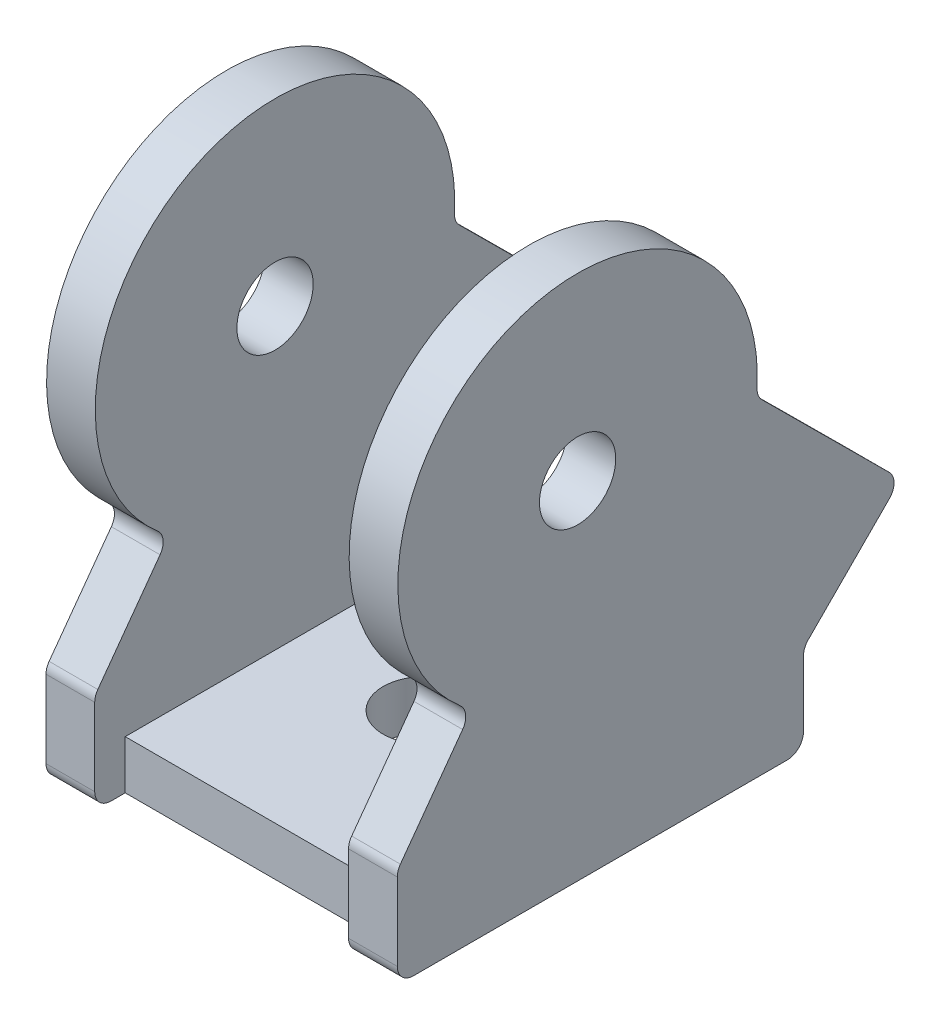
SolidWorks part; units mm, degrees
ref_plane "Front Plane" through (0, 0, 0) normal (0, 0, 1) x (1, 0, 0)
ref_plane "Top Plane" through (0, 0, 0) normal (0, 1, 0) x (1, 0, 0)
ref_plane "Right Plane" through (0, 0, 0) normal (1, 0, 0) x (0, 0, -1)
sketch "Sketch3" plane through (0, 0, 0) normal (0, 1, 0) x (1, 0, 0)
  line L0 (-15.635, 21.24) -> (15.635, -21.24) construction
  line L1 (-15.635, 21.24) -> (15.635, 21.24)
  line L2 (-15.635, 21.24) -> (-15.635, -21.24)
  line L3 (-15.635, -21.24) -> (15.635, -21.24)
  line L4 (15.635, 21.24) -> (15.635, -21.24)
  dimension "D1" = 31.27
  dimension "D2" = 42.48
extrude "Boss-Extrude1" add sketch "Sketch3" along normal blind 6 contours L1 L4 L3 L2
sketch "Sketch4" plane through (15.635, 0, 0) normal (1, 0, 0) x (0, 0, -1)
  line L0 (-24.9979, 0) -> (25.0366, 0)
  line L1 (25.0366, 0) -> (25.0366, 10.9426)
  line L3 (-24.9979, 12.19) -> (-24.9979, 0)
  line L4 (25.0366, 10.9426) -> (37.0207, 23)
  line L6 (-24.9979, 12.19) -> (-15.8175, 24.8005)
  line L7 (37.0207, 23) -> (19.2589, 40.6538)
  arc A0 (19.2589, 40.6538) -> (-15.8175, 24.8005) centre (-2.7867, 42.7) ccw
  circle A1 centre (-2.7867, 42.7) radius 4.7
  dimension "D7" = 12.6105
  dimension "D1" = 50.05
  dimension "D2" = 12.19
  dimension "D3" = 42.7
  dimension "D4" = 23
  dimension "D5" = 17
  dimension "D6" = 90
  dimension "D8" = 52.8382
extrude "Boss-Extrude2" add sketch "Sketch4" along normal blind 6
mirror "Mirror2" about plane through (0, 0, 0) normal (1, 0, 0) of "Boss-Extrude2"
sketch "Sketch6" plane through (0, 0, 0) normal (0, -1, 0) x (1, 0, 0)
  circle A0 centre (0, 0) radius 5.1
extrude "Cut-Extrude2" cut sketch "Sketch6" against normal blind 6
fillet "Fillet1" radius 2 12 edges at (-18.635, 12.19, 24.9979) (-18.635, 0, 24.9979) (18.635, 10.9426, -25.0366) (-18.635, 10.9426, -25.0366) (-18.635, 0, -25.0366) (18.635, 0, -25.0366) (18.635, 0, 24.9979) (18.635, 12.19, 24.9979) (18.635, 24.8005, 15.8175) (-18.635, 24.8005, 15.8175) (18.635, 23, -37.0207) (-18.635, 23, -37.0207)
fillet "Fillet2" radius 2 2 edges at (-18.635, 40.6538, -19.2589) (18.635, 40.6538, -19.2589)
